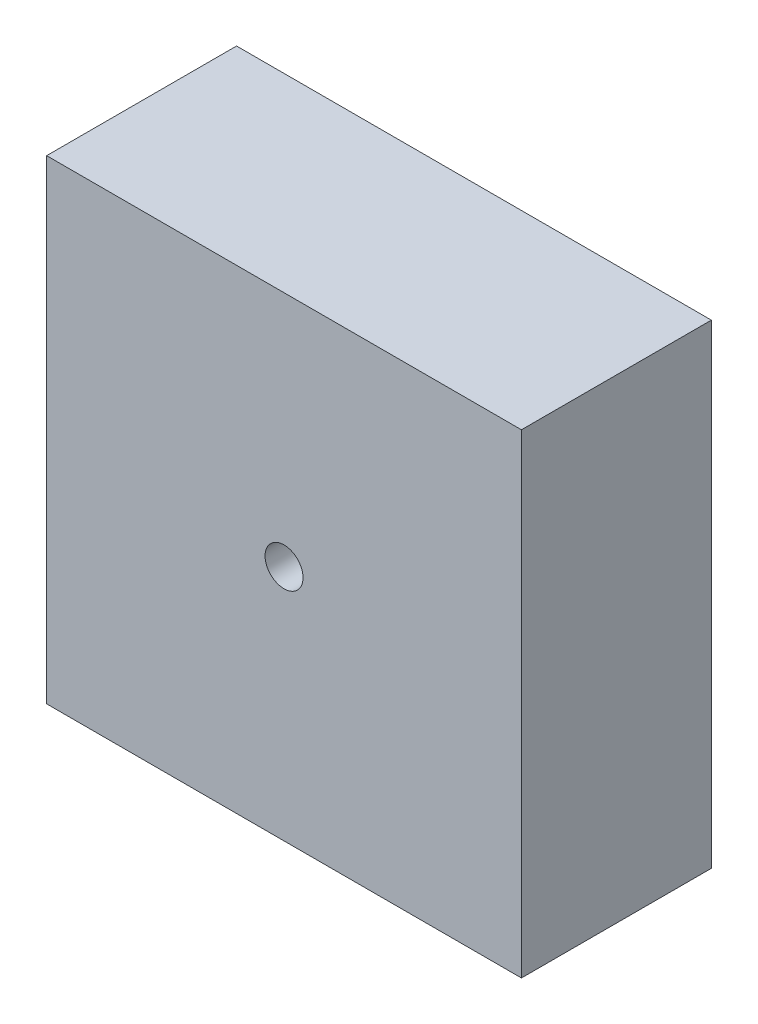
SolidWorks part; units mm, degrees
ref_plane "Front Plane" through (0, 0, 0) normal (0, 0, 1) x (1, 0, 0)
ref_plane "Top Plane" through (0, 0, 0) normal (0, 1, 0) x (1, 0, 0)
ref_plane "Right Plane" through (0, 0, 0) normal (1, 0, 0) x (0, 0, -1)
sketch "Sketch1" plane through (0, 0, 0) normal (0, 0, 1) x (1, 0, 0)
  line L1 (-25, 25) -> (25, 25)
  line L2 (-25, 25) -> (-25, -25)
  line L3 (-25, -25) -> (25, -25)
  line L4 (25, 25) -> (25, -25)
  line L5 (-25, 25) -> (25, -25) construction
  line L6 (-25, -25) -> (25, 25) construction
  circle A0 centre (0, 0) radius 2
  point P0 (0, 0)
  dimension "D3" = 4
  dimension "D1" = 50
  dimension "D2" = 50
extrude "Boss-Extrude1" add sketch "Sketch1" along normal blind 20
